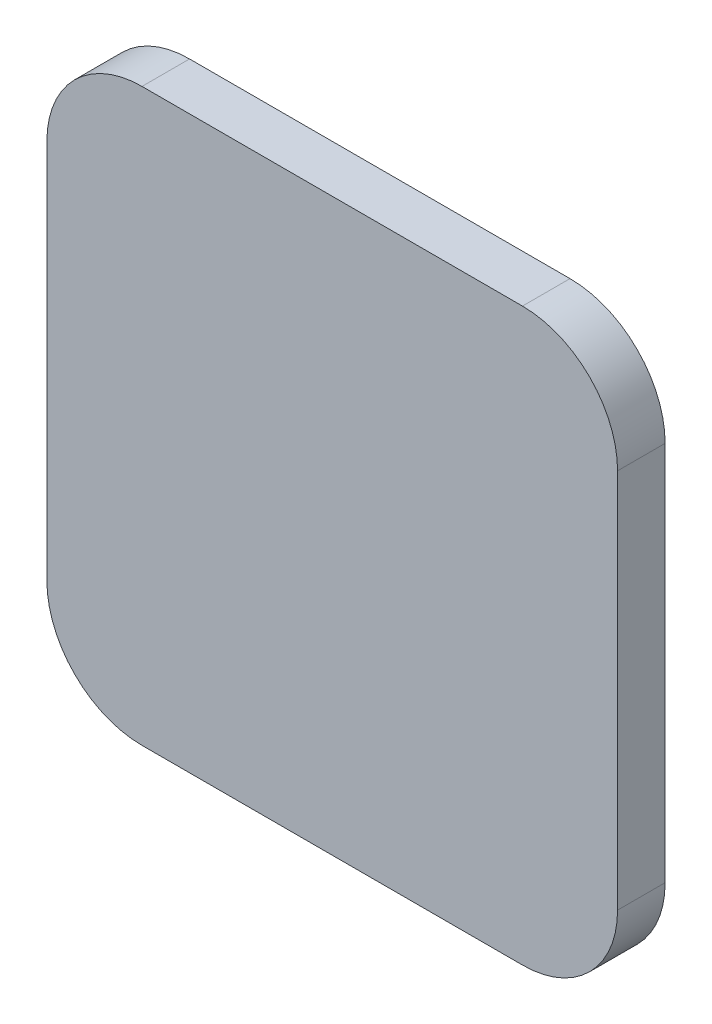
SolidWorks part; units mm, degrees
ref_plane "Front Plane" through (0, 0, 0) normal (0, 0, 1) x (1, 0, 0)
ref_plane "Top Plane" through (0, 0, 0) normal (0, 1, 0) x (1, 0, 0)
ref_plane "Right Plane" through (0, 0, 0) normal (1, 0, 0) x (0, 0, -1)
sketch "Sketch1" plane through (0, 0, 0) normal (0, 0, 1) x (1, 0, 0)
  circle A0 centre (0, 0) radius 5
  circle A1 centre (0, 0) radius 7.5
  dimension "D1" = 10
  dimension "D2" = 2.5
extrude "Boss-Extrude1" add sketch "Sketch1" along normal blind 5 contours A0 | A1
sketch "Sketch2" plane through (0, 0, 5) normal (0, 0, 1) x (1, 0, 0)
  line L1 (-15, -15) -> (15, -15)
  line L2 (-15, -15) -> (-15, 15)
  line L3 (-15, 15) -> (15, 15)
  line L4 (15, -15) -> (15, 15)
  line L5 (-15, -15) -> (15, 15) construction
  line L6 (-15, 15) -> (15, -15) construction
  point P0 (0, 0)
  dimension "D1" = 30
extrude "Boss-Extrude2" add sketch "Sketch2" along normal blind 2.5
fillet "Fillet1" radius 5 4 edges at (15, -15, 6.25) (15, 15, 6.25) (-15, 15, 6.25) (-15, -15, 6.25)
fillet "Fillet2" radius 1.3 1 edges at (7.5, 0, 5)
